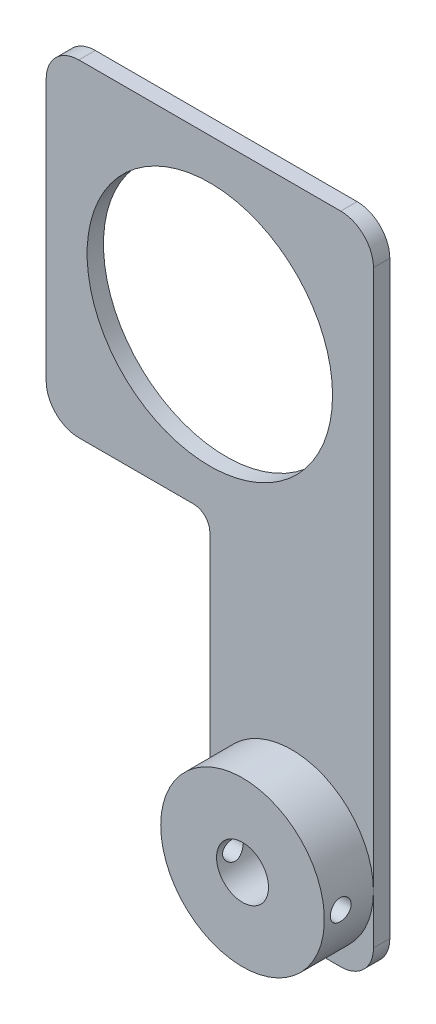
SolidWorks part; units mm, degrees
ref_plane "Alzado" through (0, 0, 0) normal (0, 0, 1) x (1, 0, 0)
ref_plane "Planta" through (0, 0, 0) normal (0, 1, 0) x (1, 0, 0)
ref_plane "Vista lateral" through (0, 0, 0) normal (1, 0, 0) x (0, 0, -1)
sketch "Croquis1" plane through (0, 0, 0) normal (0, 0, 1) x (1, 0, 0)
  line L0 (-5, 0) -> (-40, 0)
  line L1 (40, -100) -> (10, -100)
  line L2 (50, -90) -> (50, 90)
  line L3 (40, 100) -> (-40, 100)
  line L4 (-50, 10) -> (-50, 90)
  line L5 (50, -100) -> (-50, 100) construction
  line L6 (50, 100) -> (0, 0) construction
  line L7 (0, -5) -> (0, -90)
  line L8 (0, 100) -> (0, 0) construction
  arc A0 (-40, 100) -> (-50, 90) centre (-40, 90) ccw
  arc A1 (40, -100) -> (50, -90) centre (40, -90) ccw
  arc A2 (50, 90) -> (40, 100) centre (40, 90) ccw
  circle A3 centre (0, 50) radius 37.5
  arc A4 (0, -90) -> (10, -100) centre (10, -90) ccw
  arc A5 (-40, 0) -> (-50, 10) centre (-40, 10) cw
  arc A7 (0, -5) -> (-5, 0) centre (-5, -5) ccw
  point P0 (0, 0)
  dimension "D3" = 10
  dimension "D4" = 75
  dimension "D5" = 10
  dimension "D7" = 5
  dimension "D1" = 200
  dimension "D2" = 100
extrude "Saliente-Extruir1" add sketch "Croquis1" along normal blind 5
sketch "Croquis2" plane through (0, 0, 0) normal (0, 0, -1) x (-1, 0, 0)
  line L0 (0, -5) -> (0, -90) construction
  line L1 (-50, -100) -> (0, -100) construction
  line L2 (-50, -100) -> (-50, -50) construction
  line L3 (-50, -50) -> (0, -50) construction
  line L4 (0, -100) -> (0, -50) construction
  circle A0 centre (-25, -75) radius 25
  circle A1 centre (-25, -75) radius 7.9375
  dimension "D2" = 15.875
  dimension "D1" = 50
extrude "Saliente-Extruir2" add sketch "Croquis2" against normal blind 20
sketch "Croquis3" plane through (0, 0, 0) normal (1, 0, 0) x (0, 0, -1)
  line L0 (0, -75) -> (-5, -75) construction
  line L1 (0, -5) -> (0, -90) construction
  line L2 (-2.5, -75) -> (-2.5, -68.8394) construction
  circle A0 centre (10, -75) radius 3.175
  circle A1 centre (-15, -75) radius 3.175
  dimension "D1" = 6.35
extrude "Cortar-Extruir2" cut sketch "Croquis3" along normal blind 65
